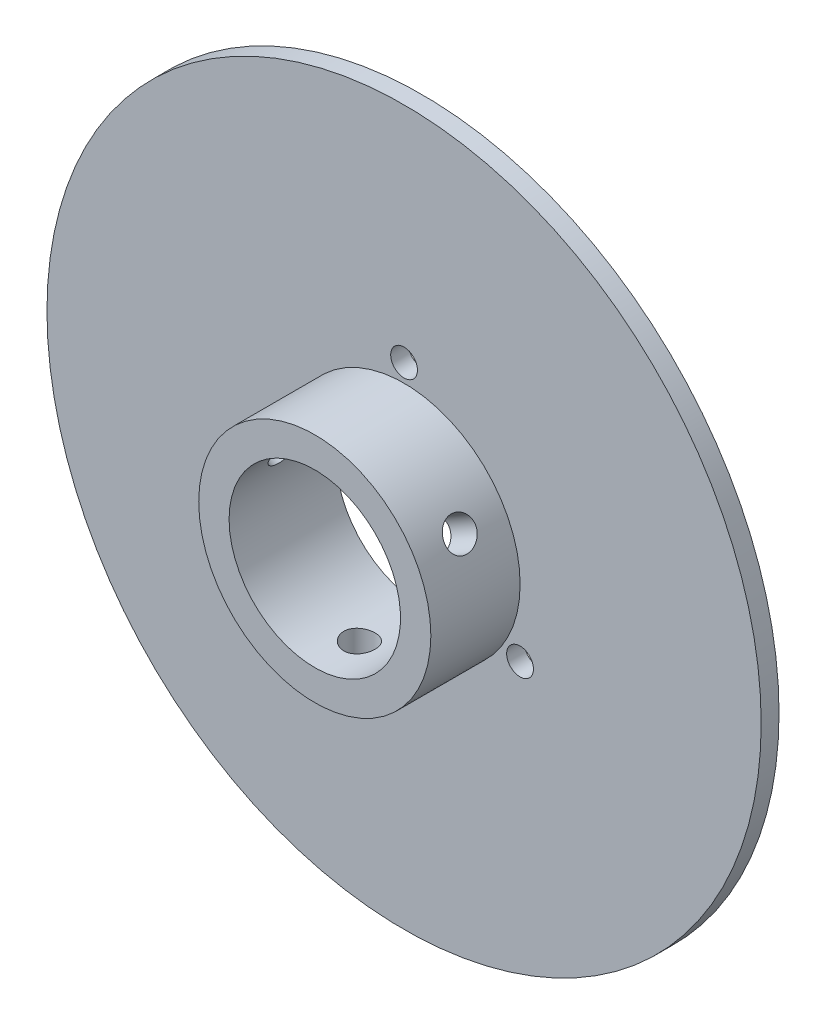
SolidWorks part; units mm, degrees
material "AISI 304"
ref_plane "Front Plane" through (0, 0, 0) normal (0, 0, 1) x (1, 0, 0)
ref_plane "Top Plane" through (0, 0, 0) normal (0, 1, 0) x (1, 0, 0)
ref_plane "Right Plane" through (0, 0, 0) normal (1, 0, 0) x (0, 0, -1)
sketch "Sketch1" plane through (0, 0, 0) normal (0, 0, 1) x (1, 0, 0)
  circle A0 centre (0, 0) radius 40
  dimension "D1" = 80
extrude "Boss-Extrude1" add sketch "Sketch1" along normal blind 2
sketch "Sketch2" plane through (0, 0, 2) normal (0, 0, 1) x (1, 0, 0)
  circle A0 centre (0, 0) radius 13
  dimension "D1" = 26
extrude "Boss-Extrude2" add sketch "Sketch2" along normal blind 10
sketch "Sketch3" plane through (0, 0, 0) normal (0, 0, -1) x (-1, 0, 0)
  circle A0 centre (0, 0) radius 9.6
  dimension "D1" = 19.2
extrude "Cut-Extrude1" cut sketch "Sketch3" against normal through all
sketch "Sketch4" plane through (0, 0, 0) normal (0, 1, 0) x (1, 0, 0)
  line L0 (0, -2) -> (0, -12) construction
  line L1 (-13, -2) -> (13, -2) construction
  line L2 (-13, -12) -> (13, -12) construction
  circle A0 centre (0, -7) radius 1.75
  dimension "D1" = 3.5
  dimension "D2" = 5
extrude "Cut-Extrude2" cut sketch "Sketch4" against normal through all
cosmetic thread "Cosmetic Thread1" parameters "D1"=3.4817, "D2"=3.5
pattern_circular "CirPattern1" count 3 over 360 about axis through (0, 0, 12) along (0, 0, -1) of "Cut-Extrude2"
sketch "Sketch5" plane through (0, 0, 0) normal (0, 0, -1) x (-1, 0, 0)
  line L0 (0, 0) -> (12.9904, -7.5) construction
  line L1 (0, 0) -> (0, -15) construction
  circle A0 centre (12.9904, -7.5) radius 1.5
  circle A1 centre (0, 0) radius 15 construction
  dimension "D1" = 3
  dimension "D2" = 30
  dimension "D3" = 60
extrude "Cut-Extrude3" cut sketch "Sketch5" against normal blind 10
cosmetic thread "Cosmetic Thread2" parameters "D1"=2, "D2"=3.6
pattern_circular "CirPattern2" count 3 over 360 about axis through (0, 0, 0) along (0, 0, 1) of "Cut-Extrude3"
